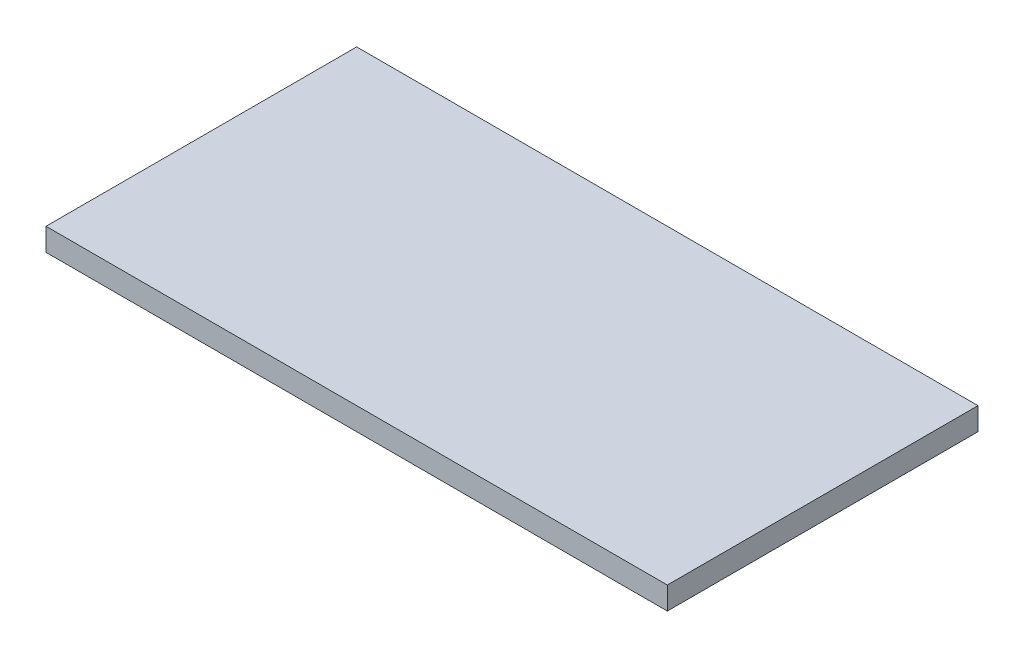
SolidWorks part; units mm, degrees
ref_plane "Alzado" through (0, 0, 0) normal (0, 0, 1) x (1, 0, 0)
ref_plane "Planta" through (0, 0, 0) normal (0, 1, 0) x (1, 0, 0)
ref_plane "Vista lateral" through (0, 0, 0) normal (1, 0, 0) x (0, 0, -1)
sketch "Croquis1" plane through (0, 0, 0) normal (0, 1, 0) x (1, 0, 0)
  line L1 (-55, 27.5) -> (55, 27.5)
  line L2 (-55, 27.5) -> (-55, -27.5)
  line L3 (-55, -27.5) -> (55, -27.5)
  line L4 (55, 27.5) -> (55, -27.5)
  line L5 (-55, 27.5) -> (55, -27.5) construction
  line L6 (-55, -27.5) -> (55, 27.5) construction
  point P0 (0, 0)
  dimension "D1" = 110
  dimension "D2" = 55
extrude "Saliente-Extruir1" add sketch "Croquis1" along normal mid plane 4
